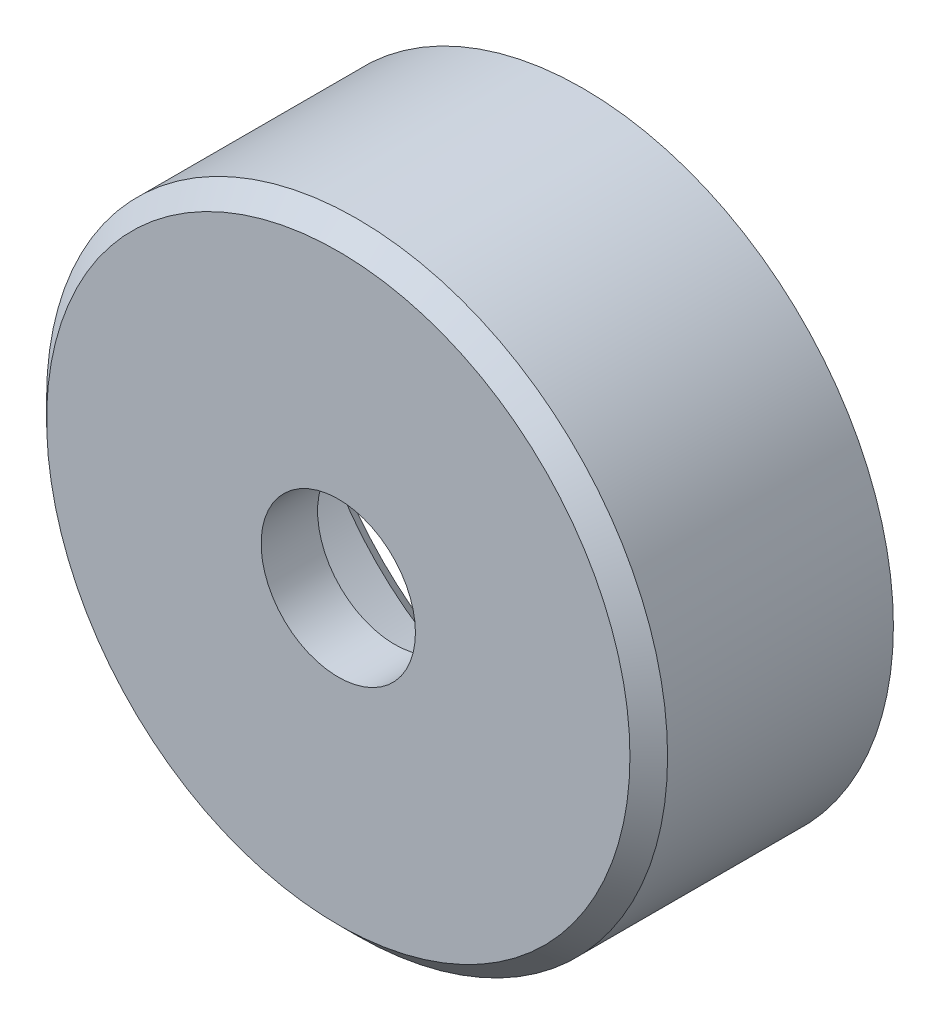
SolidWorks part; units mm, degrees
ref_plane "Front" through (0, 0, 0) normal (0, 0, 1) x (1, 0, 0)
ref_plane "Top" through (0, 0, 0) normal (0, 1, 0) x (1, 0, 0)
ref_plane "Right" through (0, 0, 0) normal (1, 0, 0) x (0, 0, -1)
sketch "Esquisse1" plane through (0, 0, 0) normal (0, 0, 1) x (1, 0, 0)
  circle A0 centre (0, 0) radius 14
  circle A1 centre (0, 0) radius 16.5
  dimension "D1" = 28
  dimension "D2" = 33
extrude "Boss.-Extru.1" add sketch "Esquisse1" along normal blind 10
sketch "Esquisse2" plane through (0, 0, 10) normal (0, 0, 1) x (1, 0, 0)
  circle A1 centre (0, 0) radius 16.5
extrude "Boss.-Extru.2" add sketch "Esquisse2" along normal blind 3
chamfer "Chanfrein1" distance 1 angle 45 1 edges at (14, 0, 0)
sketch "Esquisse3" plane through (0, 0, 13) normal (0, 0, 1) x (1, 0, 0)
  circle A0 centre (0, 0) radius 4.1
  dimension "D1" = 8.2
extrude "Enlèv. mat.-Extru.1" cut sketch "Esquisse3" against normal through all both and the other way through all
chamfer "Chanfrein2" distance 1 angle 45 1 edges at (16.5, 0, 13)
